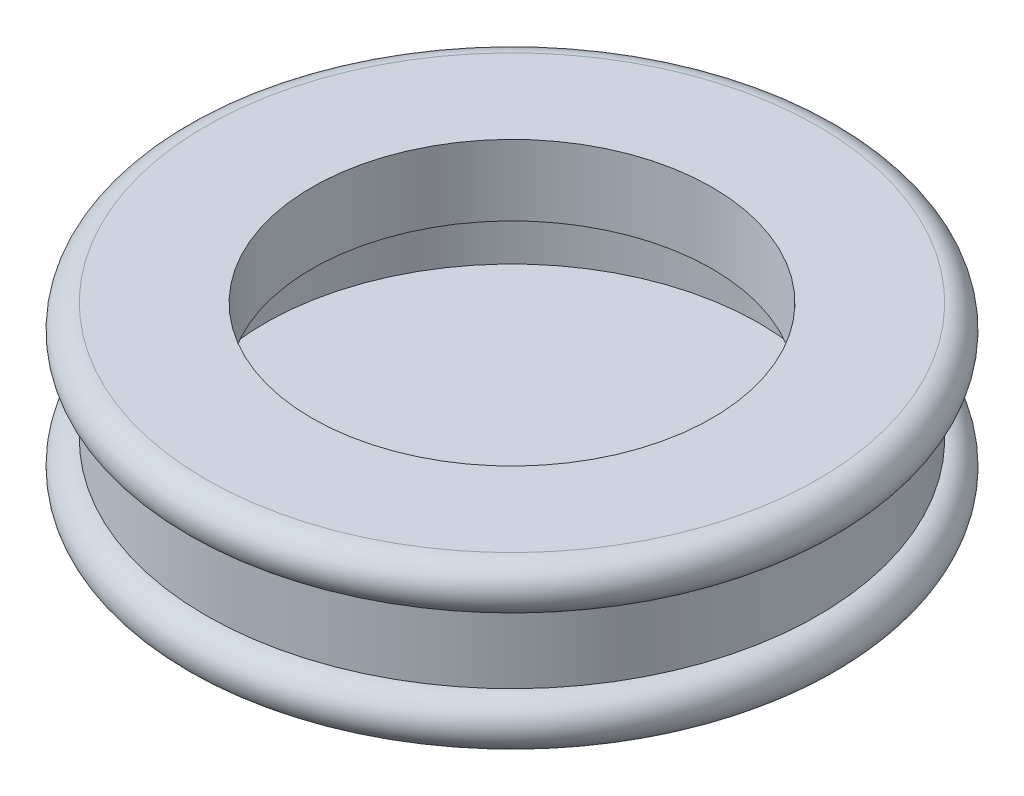
SolidWorks part; units mm, degrees
ref_plane "Ebene vorne" through (0, 0, 0) normal (0, 0, 1) x (1, 0, 0)
ref_plane "Ebene oben" through (0, 0, 0) normal (0, 1, 0) x (1, 0, 0)
ref_plane "Ebene rechts" through (0, 0, 0) normal (1, 0, 0) x (0, 0, -1)
sketch "Skizze1" plane through (0, 0, 0) normal (0, 0, 1) x (1, 0, 0)
  line L0 (0, 0) -> (13.1504, 2)
  line L1 (13, 3.9886) -> (13, 6.9984)
  line L2 (13, 8.9984) -> (8.5, 8.9984)
  line L3 (0, 0) -> (0, 2.9984) construction
  line L4 (0, 2.9984) -> (10.5, 2.9984)
  line L5 (10.5, 2.9984) -> (10.5, 5.9984)
  line L6 (10.5, 5.9984) -> (8.5, 5.9984)
  line L7 (8.5, 5.9984) -> (8.5, 8.9984)
  line L8 (0, 0) -> (0, 2.9984)
  arc A0 (13.1504, 2) -> (13, 3.9886) centre (13, 2.9886) ccw
  arc A1 (13, 6.9984) -> (13, 8.9984) centre (13, 7.9984) ccw
  dimension "D3" = 28
  dimension "D6" = 1
  dimension "D1" = 3
  dimension "D2" = 8.5
  dimension "D4" = 7
  dimension "D5" = 3
  dimension "D7" = 2
  dimension "D8" = 2
revolve "Rotation1" add sketch "Skizze1" angle 360 about L3
